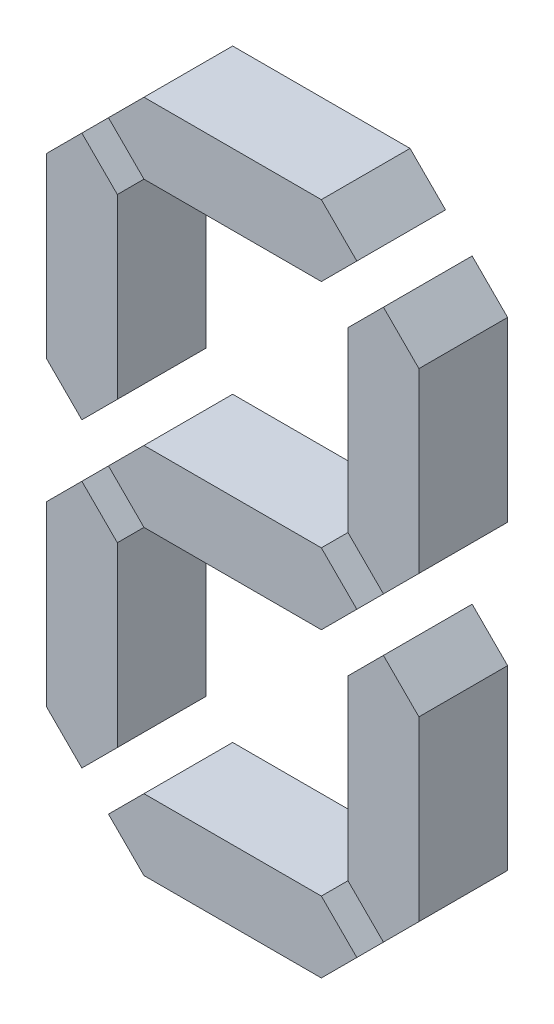
SolidWorks part; units mm, degrees
ref_plane "Front Plane" through (0, 0, 0) normal (0, 0, 1) x (1, 0, 0)
ref_plane "Top Plane" through (0, 0, 0) normal (0, 1, 0) x (1, 0, 0)
ref_plane "Right Plane" through (0, 0, 0) normal (1, 0, 0) x (0, 0, -1)
sketch "Sketch1" plane through (0, 0, 0) normal (0, 0, 1) x (1, 0, 0)
  line L0 (-2.1, 2.7) -> (-1.7, 3.1)
  line L1 (-1, 0.4) -> (1, 0.4)
  line L2 (1.4, 0) -> (1, -0.4)
  line L3 (-1, -0.4) -> (1, -0.4)
  line L4 (1.7, -0.3) -> (2.1, -0.7)
  line L5 (-1, 0.4) -> (1, -0.4) construction
  line L6 (-1, -0.4) -> (1, 0.4) construction
  line L7 (-2.1, -2.7) -> (-1.7, -3.1)
  line L8 (1.3, -0.7) -> (1.3, -2.7)
  line L10 (2.1, -0.7) -> (2.1, -2.7)
  line L11 (1, -3) -> (-1, -3)
  line L12 (1.7, -3.1) -> (2.1, -2.7)
  line L13 (1, -3.8) -> (-1, -3.8)
  line L15 (-1.3, -2.7) -> (-1.7, -3.1)
  line L16 (1.3, 0.7) -> (1.3, 2.7)
  line L17 (2.1, 0.7) -> (1.7, 0.3)
  line L18 (2.1, 0.7) -> (2.1, 2.7)
  line L19 (1, 3) -> (-1, 3)
  line L20 (1.7, 3.1) -> (2.1, 2.7)
  line L21 (1, 3.8) -> (-1, 3.8)
  line L22 (-1, 0.4) -> (-1.4, 0)
  line L23 (-2.1, 0.7) -> (-1.7, 0.3)
  line L24 (-1.3, 2.7) -> (-1.3, 0.7)
  line L25 (-1, -3) -> (-1.4, -3.4)
  line L26 (-2.1, 2.7) -> (-2.1, 0.7)
  line L28 (-1.3, -2.7) -> (-1.3, -0.7)
  line L29 (1, -3.8) -> (1.4, -3.4)
  line L30 (-2.1, -2.7) -> (-2.1, -0.7)
  line L31 (-1.3, 2.7) -> (-1.7, 3.1)
  line L32 (-1, 3) -> (-1.4, 3.4)
  line L33 (-1.4, 3.4) -> (-1, 3.8)
  line L34 (-1.3, 0.7) -> (-1.7, 0.3)
  line L35 (-1.3, -0.7) -> (-1.7, -0.3)
  line L36 (1, 3.8) -> (1.4, 3.4)
  line L37 (1.3, 2.7) -> (1.7, 3.1)
  line L38 (1, 3) -> (1.4, 3.4)
  line L39 (1, 0.4) -> (1.4, 0)
  line L40 (1.3, 0.7) -> (1.7, 0.3)
  line L41 (1.3, -0.7) -> (1.7, -0.3)
  line L42 (-1.7, -0.3) -> (-2.1, -0.7)
  line L43 (-1.4, 0) -> (-1, -0.4)
  line L44 (1.3, -2.7) -> (1.7, -3.1)
  line L45 (1, -3) -> (1.4, -3.4)
  line L46 (-1.4, -3.4) -> (-1, -3.8)
  point P0 (0, 0)
  dimension "D1" = 2
extrude "Boss-Extrude1" add sketch "Sketch1" along normal blind 1
